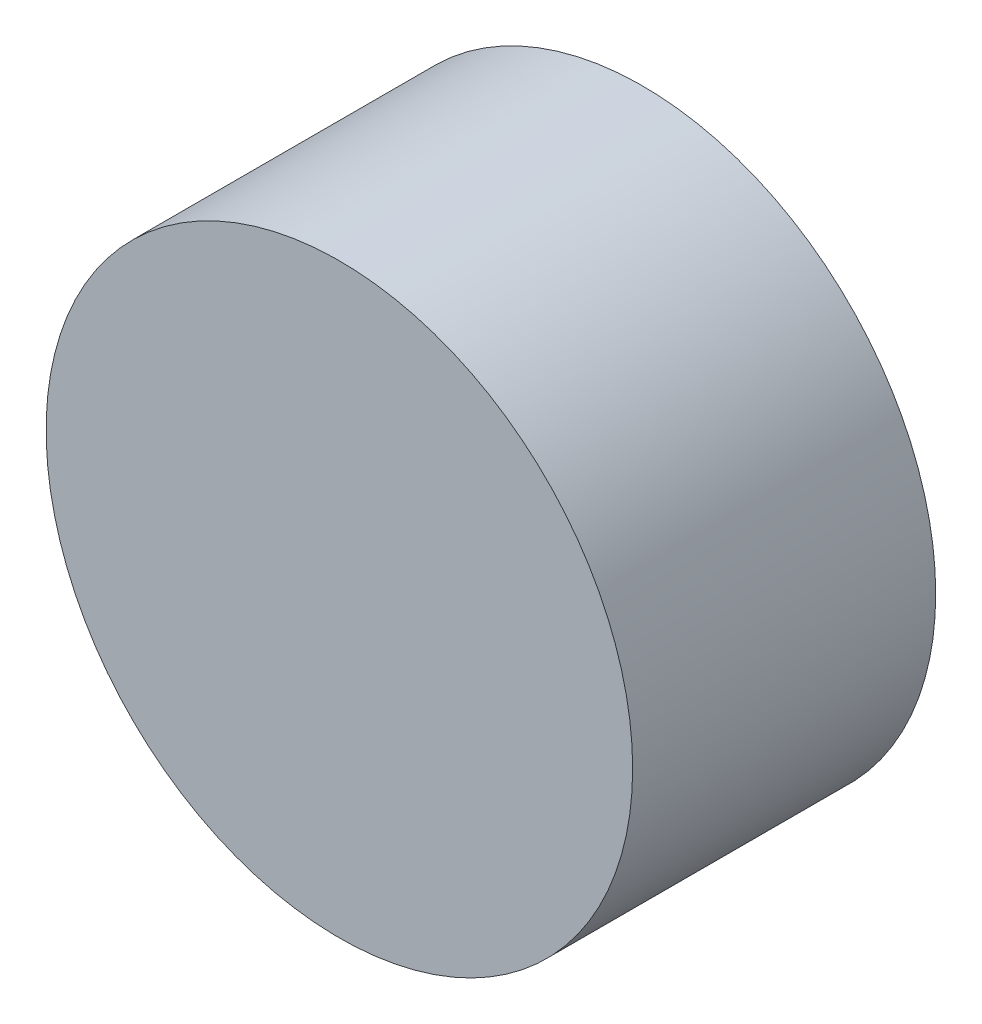
SolidWorks part; units mm, degrees
material "ABS PC"
ref_plane "Front Plane" through (0, 0, 0) normal (0, 0, 1) x (1, 0, 0)
ref_plane "Top Plane" through (0, 0, 0) normal (0, 1, 0) x (1, 0, 0)
ref_plane "Right Plane" through (0, 0, 0) normal (1, 0, 0) x (0, 0, -1)
sketch "Sketch1" plane through (0, 0, 0) normal (0, 0, 1) x (1, 0, 0)
  circle A0 centre (-15.8218, 16.0037) radius 30
extrude "Boss-Extrude1" add sketch "Sketch1" along normal blind 31 contours A0
